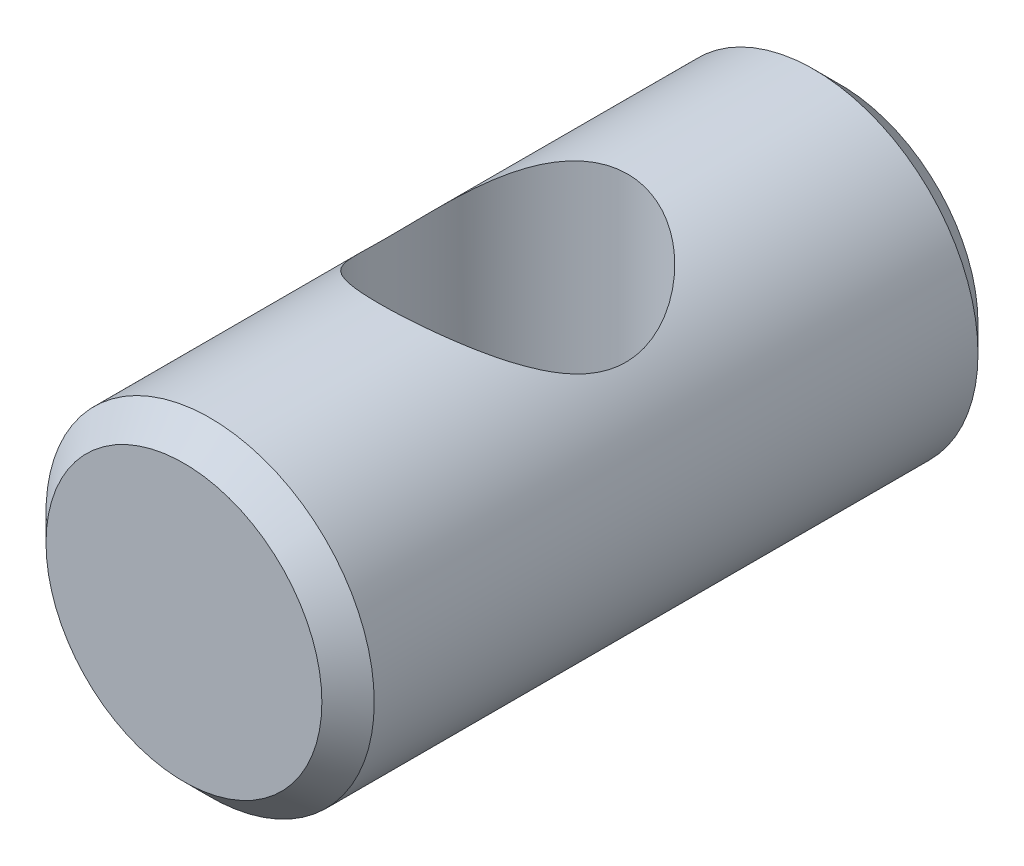
SolidWorks part; units mm, degrees
ref_plane "Front Plane" through (0, 0, 0) normal (0, 0, 1) x (1, 0, 0)
ref_plane "Top Plane" through (0, 0, 0) normal (0, 1, 0) x (1, 0, 0)
ref_plane "Right Plane" through (0, 0, 0) normal (1, 0, 0) x (0, 0, -1)
sketch "Sketch1" plane through (0, 0, 0) normal (0, 0, 1) x (1, 0, 0)
  circle A0 centre (0, 0) radius 4.765
  dimension "D1" = 9.53
extrude "Boss-Extrude1" add sketch "Sketch1" along normal mid plane 19.05
sketch "Sketch2" plane through (0, 0, 0) normal (0, 1, 0) x (1, 0, 0)
  line L0 (0, -9.525) -> (0, 0) construction
  line L1 (-4.765, -9.525) -> (4.765, -9.525) construction
  line L2 (-4.765, 0) -> (4.765, 0) construction
  line L3 (-4.765, 9.525) -> (-4.765, -9.525) construction
  line L4 (4.765, -9.525) -> (4.765, 9.525) construction
  circle A0 centre (-0.125, 0) radius 3.43
  dimension "D2" = 6.86
  dimension "D1" = 0.25
extrude "Cut-Extrude1" cut sketch "Sketch2" against normal through all both and the other way through all
chamfer "Chamfer1" distance 0.76 angle 45 2 edges at (4.765, 0, 9.525) (4.765, 0, -9.525)
